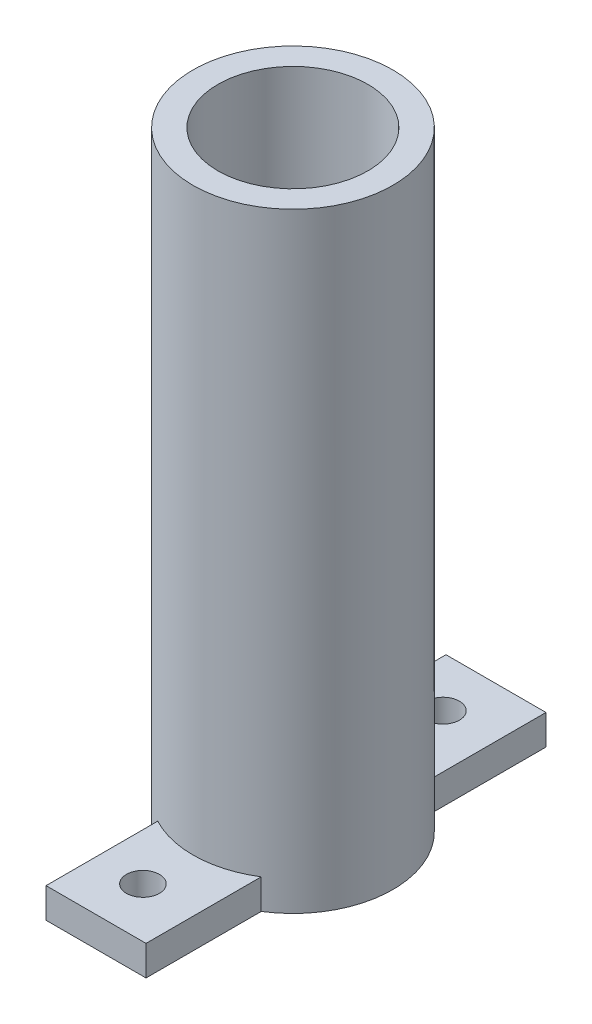
SolidWorks part; units mm, degrees
ref_plane "Plan de face" through (0, 0, 0) normal (0, 0, 1) x (1, 0, 0)
ref_plane "Plan de dessus" through (0, 0, 0) normal (0, 1, 0) x (1, 0, 0)
ref_plane "Plan de droite" through (0, 0, 0) normal (1, 0, 0) x (0, 0, -1)
sketch "Esquisse1" plane through (0, 0, 0) normal (0, 1, 0) x (1, 0, 0)
  line L0 (0, 0) -> (0, 20) construction
  line L1 (0, 20) -> (5.3072, 20)
  line L2 (0, 20) -> (-4.6928, 20)
  line L3 (0, 0) -> (0, -20) construction
  line L4 (-4.6928, 20) -> (-4.6928, 8.8305)
  line L5 (5.3072, 20) -> (5.3072, 8.4755)
  line L6 (0, -20) -> (5.3072, -20)
  line L7 (0, -20) -> (-4.6928, -20)
  line L8 (-4.6928, -20) -> (-4.6928, -8.8305)
  line L9 (5.3072, -20) -> (5.3072, -8.4755)
  arc A0 (-4.6928, 8.8305) -> (-4.6928, -8.8305) centre (0, 0) ccw
  circle A1 centre (0, 0) radius 7.5
  circle A2 centre (0, 15) radius 1.65
  arc A3 (5.3072, -8.4755) -> (5.3072, 8.4755) centre (0, 0) ccw
  circle A4 centre (0, -15) radius 1.65
  dimension "D1" = 20
  dimension "D2" = 15
  dimension "D9" = 3.3
  dimension "D11" = 3.3
  dimension "D3" = 20
  dimension "D4" = 10
  dimension "D5" = 11.5245
  dimension "D6" = 11.5245
  dimension "D7" = 20
  dimension "D8" = 10
  dimension "D10" = 5
  dimension "D12" = 5
extrude "Boss.-Extru.1" add sketch "Esquisse1" against normal blind 3
sketch "Esquisse2" plane through (0, 0, 0) normal (0, 1, 0) x (1, 0, 0)
  circle A0 centre (0, 0) radius 10
  circle A1 centre (0, 0) radius 7.5
  dimension "D1" = 20
  dimension "D2" = 15
extrude "Boss.-Extru.2" add sketch "Esquisse2" along normal blind 58
